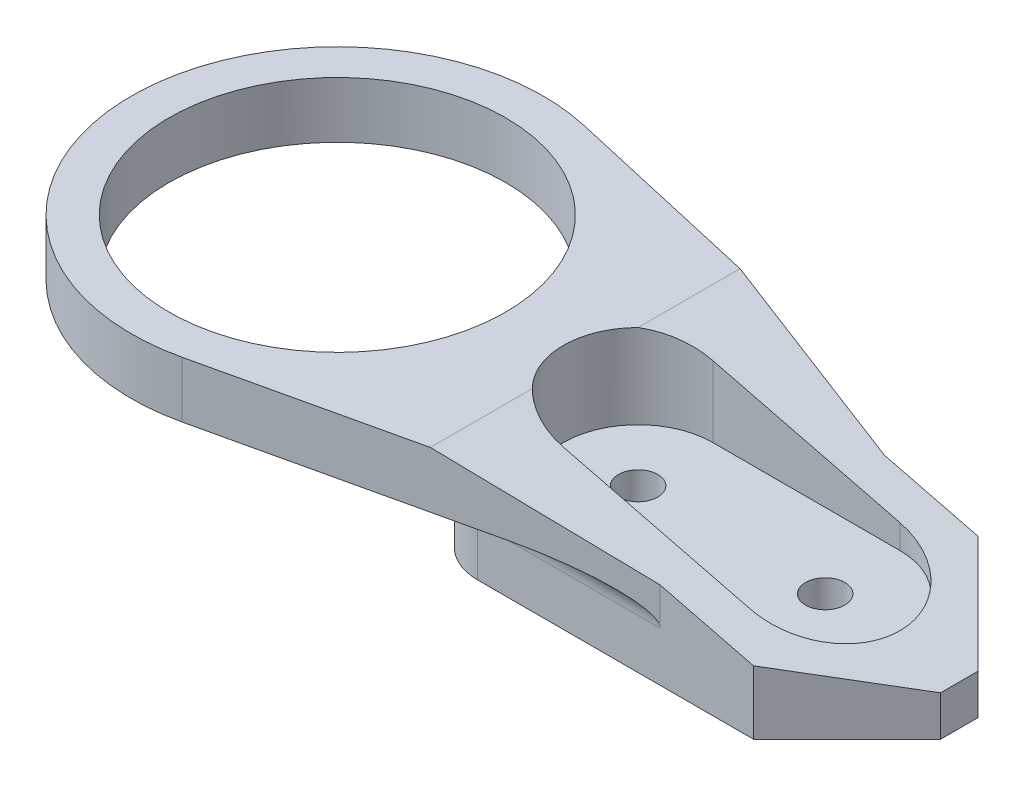
SolidWorks part; units mm, degrees
ref_plane "Front Plane" through (0, 0, 0) normal (0, 0, 1) x (1, 0, 0)
ref_plane "Top Plane" through (0, 0, 0) normal (0, 1, 0) x (1, 0, 0)
ref_plane "Right Plane" through (0, 0, 0) normal (1, 0, 0) x (0, 0, -1)
sketch "Sketch1" plane through (0, 0, 0) normal (0, 0, 1) x (1, 0, 0)
  line L0 (0, 0) -> (0, 7.15)
  line L1 (0, 7.15) -> (25, 7.15)
  line L2 (25, 7.15) -> (25, 0)
  line L3 (25, 0) -> (0, 0)
extrude "Boss-Extrude1" add sketch "Sketch1" along normal blind 12
sketch "Sketch2" plane through (0, 7.15, 0) normal (0, 1, 0) x (1, 0, 0)
  line L0 (0, -6) -> (-8.25, -6) construction
  line L1 (0, -12) -> (0, 0) construction
  line L3 (25, 0) -> (0, 0) construction
  line L5 (25, -12) -> (0, -12) construction
  line L8 (15, -6) -> (15, 0)
  line L11 (15, 0) -> (-5.8049, 4.7375)
  line L12 (15, -6) -> (15, -12)
  line L13 (15, -12) -> (-5.8049, -16.7375)
  arc A6 (-5.8049, 4.7375) -> (-5.8049, -16.7375) centre (-8.25, -6) ccw
extrude "Boss-Extrude2" add sketch "Sketch2" against normal blind 3
sketch "Sketch3" plane through (0, 4.15, 0) normal (0, -1, 0) x (1, 0, 0)
  line L0 (-8.25, 6) -> (2.25, 6) construction
  line L1 (2.25, 6) -> (2.25, 12)
  line L2 (0, 12) -> (25, 12) construction
  line L3 (2.25, 12) -> (0, 12)
  line L4 (0, 12) -> (0, 0)
  line L5 (0, 0) -> (2.25, 0)
  line L6 (15, 0) -> (0, 0) construction
  line L7 (2.25, 0) -> (2.25, 6)
  circle A0 centre (-8.25, 6) radius 11.0124 construction
extrude "Cut-Extrude1" cut sketch "Sketch3" along normal blind 21
sketch "Sketch4" plane through (0, 4.15, 0) normal (0, -1, 0) x (1, 0, 0)
  circle A2 centre (-8.25, 6) radius 9
extrude "Cut-Extrude2" cut sketch "Sketch4" against normal blind 10
chamfer "Chamfer1" distance 5 distance2 20 1 edges at (25, 7.15, 6)
chamfer "Chamfer2" distance 5 angle 45 2 edges at (25, 1.075, 12) (25, 1.075, 0)
sketch "Sketch6" plane through (0, 7.15, 0) normal (0, 1, 0) x (1, 0, 0)
  line L0 (-0.0037, -6) -> (7.8299, -6) construction
  line L1 (7.8299, -6) -> (17.8299, -6) construction
  circle A0 centre (-8.5537, -6) radius 8.55 construction
  circle A1 centre (7.8299, -6) radius 1.05
  circle A2 centre (17.8299, -6) radius 1.05
  dimension "D1" = 10
extrude "Cut-Extrude3" cut sketch "Sketch6" against normal blind 10
sketch "Sketch7" plane through (0, 7.15, 0) normal (0, 1, 0) x (1, 0, 0)
  line L0 (7.8299, -2) -> (17.8299, -2)
  line L1 (17.8299, -10) -> (7.8299, -10)
  arc A0 (7.8299, -2) -> (7.8299, -10) centre (7.8299, -6) ccw
  arc A1 (17.8299, -10) -> (17.8299, -2) centre (17.8299, -6) ccw
extrude "Cut-Extrude4" cut sketch "Sketch7" against normal blind 4.5
fillet "Fillet1" radius 3 2 edges at (2.25, 2.075, 12) (2.25, 2.075, 0)
fillet "Fillet2" radius 1.5 5 edges at (10.125, 4.15, 12) (3.1287, 4.15, 11.1213) (2.25, 4.15, 6) (3.1287, 4.15, 0.8787) (10.125, 4.15, 0)
